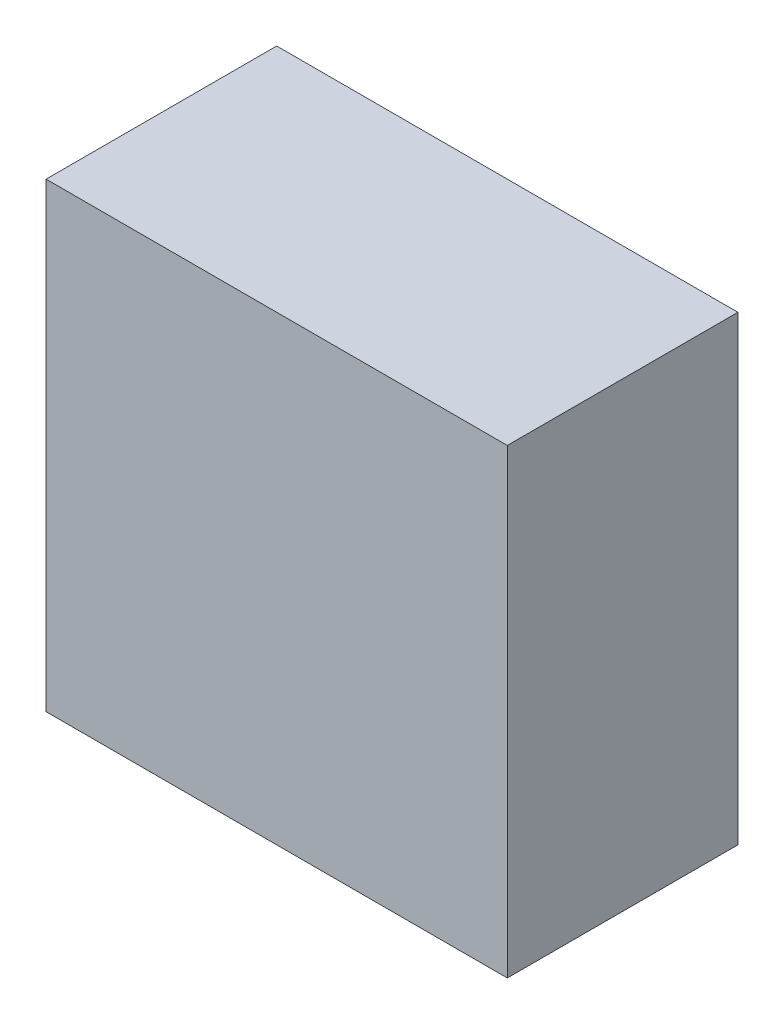
SolidWorks part; units mm, degrees
ref_plane "Přední rovina" through (0, 0, 0) normal (0, 0, 1) x (1, 0, 0)
ref_plane "Horní rovina" through (0, 0, 0) normal (0, 1, 0) x (1, 0, 0)
ref_plane "Pravá rovina" through (0, 0, 0) normal (1, 0, 0) x (0, 0, -1)
sketch "Skica1" plane through (0, 0, 0) normal (0, 0, 1) x (1, 0, 0)
  line L1 (-10, -10) -> (10, -10)
  line L2 (-10, -10) -> (-10, 10)
  line L3 (-10, 10) -> (10, 10)
  line L4 (10, -10) -> (10, 10)
  line L5 (-10, -10) -> (10, 10) construction
  line L6 (-10, 10) -> (10, -10) construction
  point P0 (0, 0)
  dimension "D1" = 20
  dimension "D2" = 20
extrude "Přidat vysunutím1" add sketch "Skica1" along normal blind 10
sketch "Skica2" plane through (0, 0, 0) normal (0, 0, -1) x (-1, 0, 0)
  line L1 (-8.5, -8.5) -> (8.5, -8.5)
  line L2 (-8.5, -8.5) -> (-8.5, 8.5)
  line L3 (-8.5, 8.5) -> (8.5, 8.5)
  line L4 (8.5, -8.5) -> (8.5, 8.5)
  line L5 (-8.5, -8.5) -> (8.5, 8.5) construction
  line L6 (-8.5, 8.5) -> (8.5, -8.5) construction
  point P0 (0, 0)
  dimension "D1" = 17
  dimension "D2" = 17
extrude "Odebrat vysunutím1" cut sketch "Skica2" against normal blind 7.5
sketch "Skica3" plane through (0, 0, 7.5) normal (0, 0, -1) x (-1, 0, 0)
  circle A0 centre (0, 0) radius 2.65
  dimension "D1" = 5.3
extrude "Přidat vysunutím2" add sketch "Skica3" along normal blind 7.5
sketch "Skica4" plane through (0, 0, 0) normal (0, 0, -1) x (-1, 0, 0)
  line L0 (-0.585, 2.05) -> (0.585, 2.05)
  line L1 (0.585, 2.05) -> (0.585, 0.585)
  line L2 (0.585, 0.585) -> (2.05, 0.585)
  line L3 (2.05, 0.585) -> (2.05, -0.585)
  line L4 (0, 0) -> (0, 2.65) construction
  line L5 (-2.05, 0.585) -> (-2.05, -0.585)
  line L6 (-0.585, 0.585) -> (-2.05, 0.585)
  line L7 (-0.585, 2.05) -> (-0.585, 0.585)
  line L8 (0, 0) -> (2.65, 0) construction
  line L9 (0.585, -0.585) -> (2.05, -0.585)
  line L10 (0.585, -2.05) -> (0.585, -0.585)
  line L11 (-0.585, -2.05) -> (0.585, -2.05)
  line L12 (-0.585, -2.05) -> (-0.585, -0.585)
  line L13 (-0.585, -0.585) -> (-2.05, -0.585)
  circle A0 centre (0, 0) radius 2.65 construction
  circle A1 centre (0, 0) radius 2.65 construction
  point P12 (-5.2021, 1.0843)
  point P15 (0, 2.05)
  point P19 (2.05, 0)
  point P24 (-2.05, 0)
  point P25 (-1.109, 3.4628)
  dimension "D1" = 0.585
  dimension "D2" = 0.585
  dimension "D3" = 2.05
  dimension "D4" = 2.05
extrude "Odebrat vysunutím2" cut sketch "Skica4" against normal blind 7.5
